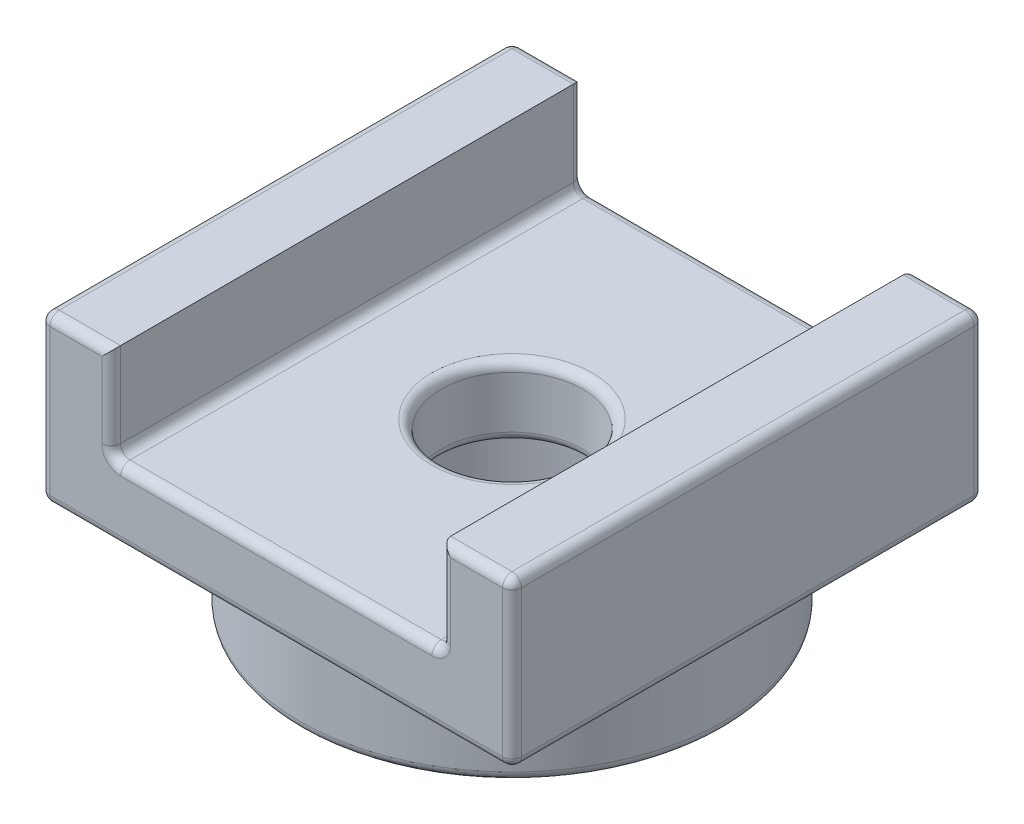
SolidWorks part; units mm, degrees
ref_plane "Alzado" through (0, 0, 0) normal (0, 0, 1) x (1, 0, 0)
ref_plane "Planta" through (0, 0, 0) normal (0, 1, 0) x (1, 0, 0)
ref_plane "Vista lateral" through (0, 0, 0) normal (1, 0, 0) x (0, 0, -1)
sketch "Croquis1" plane through (0, 0, 0) normal (0, 1, 0) x (1, 0, 0)
  line L1 (5, 5) -> (-5, 5)
  line L2 (5, 5) -> (5, -5)
  line L3 (5, -5) -> (-5, -5)
  line L4 (-5, 5) -> (-5, -5)
  circle A0 centre (0, 0) radius 1.5
  point P0 (0, 0)
  dimension "D3" = 3
  dimension "D1" = 10
  dimension "D2" = 10
extrude "Saliente-Extruir1" add sketch "Croquis1" along normal blind 1.5
sketch "Croquis2" plane through (0, 1.5, 0) normal (0, 1, 0) x (1, 0, 0)
  line L0 (-5, -5) -> (5, -5) construction
  line L1 (-5, 5) -> (-3.5, 5)
  line L2 (-5, 5) -> (-5, -5)
  line L3 (-5, -5) -> (-3.5, -5)
  line L4 (-3.5, 5) -> (-3.5, -5)
  line L5 (0, 0) -> (0, 2.0205)
  line L6 (3.5, 5) -> (3.5, -5)
  line L7 (5, -5) -> (3.5, -5)
  line L8 (5, 5) -> (5, -5)
  line L9 (5, 5) -> (3.5, 5)
  line M3 (-5, 5) -> (-5, -5)
  line M4 (-5, -5) -> (5, -5)
  line M5 (5, -5) -> (5, 5)
  line M6 (5, 5) -> (-5, 5)
  dimension "D1" = 1.5
extrude "Saliente-Extruir2" add sketch "Croquis2" along normal blind 2 contours L4 M6 M3 M4 | L6 M6 M4 M5
sketch "Croquis3" plane through (0, 0, 0) normal (0, -1, 0) x (1, 0, 0)
  circle A0 centre (0, 0) radius 4.5
  circle A1 centre (0, 0) radius 3
  dimension "D1" = 9
  dimension "D2" = 6
extrude "Saliente-Extruir3" add sketch "Croquis3" along normal blind 2
fillet "Redondeo1" radius 0.2 4 edges at (0, -2, -3) (0, 0, -4.5) (0, 0, -3) (0, -2, -4.5)
fillet "Redondeo3" radius 0.2 24 edges at (3.5, 1.5, 0) (4.25, 3.5, -5) (4.25, 3.5, 5) (5, 3.5, 0) (3.5, 2.5, 5) (3.5, 2.5, -5) (-4.25, 3.5, -5) (-4.25, 3.5, 5) (-5, 3.5, 0) (0, 0, 1.5) (0, 1.5, 1.5) (-5, 0, 0) (0, 0, 5) (0, 0, -5) (-5, 1.75, -5) (5, 1.75, -5) (-5, 1.75, 5) (5, 0, 0) (5, 1.75, 5)
